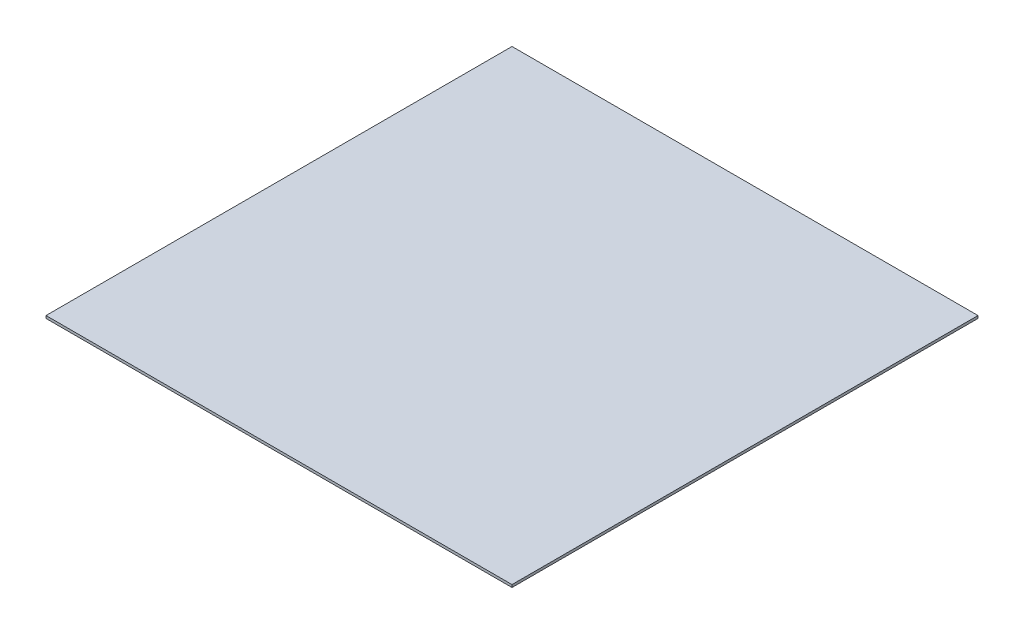
SolidWorks part; units mm, degrees
ref_plane "Front Plane" through (0, 0, 0) normal (0, 0, 1) x (1, 0, 0)
ref_plane "Top Plane" through (0, 0, 0) normal (0, 1, 0) x (1, 0, 0)
ref_plane "Right Plane" through (0, 0, 0) normal (1, 0, 0) x (0, 0, -1)
sketch "Sketch1" plane through (0, 0, 0) normal (0, 1, 0) x (1, 0, 0)
  line L5 (-273, 273) -> (273, 273)
  line L6 (-273, 273) -> (-273, -273)
  line L11 (-273, -273) -> (273, -273)
  line L12 (273, 273) -> (273, -273)
  line L13 (-273, 273) -> (273, -273) construction
  line L14 (-273, -273) -> (273, 273) construction
  point P0 (0, 0)
  dimension "D1" = 546
  dimension "D2" = 546
extrude "Boss-Extrude1" add sketch "Sketch1" along normal blind 3
